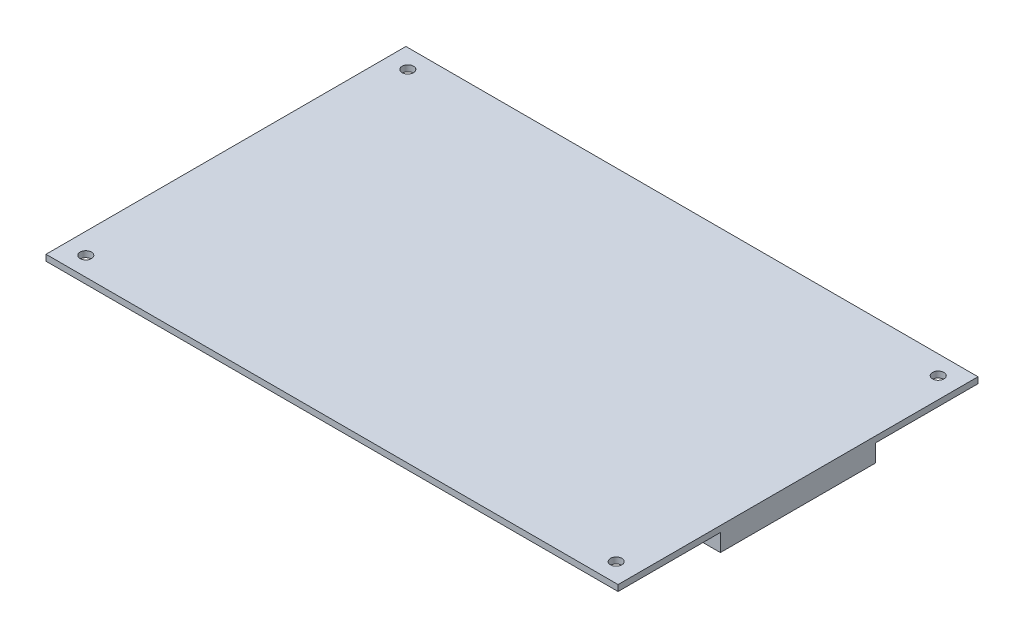
SolidWorks part; units mm, degrees
ref_plane "前视基准面" through (0, 0, 0) normal (0, 0, 1) x (1, 0, 0)
ref_plane "上视基准面" through (0, 0, 0) normal (0, 1, 0) x (1, 0, 0)
ref_plane "右视基准面" through (0, 0, 0) normal (1, 0, 0) x (0, 0, -1)
other "Configuration Table"
sketch "草图1" plane through (0, 0, 0) normal (0, 1, 0) x (1, 0, 0)
  line L1 (0, 0) -> (151, 0)
  line L2 (0, 0) -> (0, -95)
  line L3 (0, -95) -> (151, -95)
  line L4 (151, 0) -> (151, -95)
  dimension "D1" = 151
  dimension "D2" = 95
extrude "凸台-拉伸1" add sketch "草图1" along normal blind 1.6
sketch "草图2" plane through (0, 0, 0) normal (-1, 0, 0) x (0, 0, 1)
  line L0 (0, 0) -> (95, 0) construction
  line L1 (27, 0) -> (68, 0)
  line L2 (27, 0) -> (27, -4.6)
  line L3 (27, -4.6) -> (68, -4.6)
  line L4 (68, 0) -> (68, -4.6)
  line L5 (47.5, 1.6) -> (47.5, -20.1889) construction
  line L6 (0, 1.6) -> (95, 1.6) construction
  dimension "D1" = 4.6
  dimension "D2" = 41
extrude "凸台-拉伸2" add sketch "草图2" along direction (-1, 0, 0) on the side against the normal up to surface (151 mm away)
sketch "草图3" plane through (0, 1.6, 0) normal (0, 1, 0) x (1, 0, 0)
  line L0 (0, -47.5) -> (167.1753, -47.5) construction
  line L1 (0, 0) -> (0, -95) construction
  line L2 (75.5, 0) -> (75.5, -99.7613) construction
  line L3 (151, 0) -> (0, 0) construction
  circle A0 centre (5.5, -5) radius 1.5
  circle A1 centre (5.5, -90) radius 1.5
  circle A2 centre (145.5, -90) radius 1.5
  circle A3 centre (145.5, -5) radius 1.5
  dimension "D1" = 3
  dimension "D2" = 85
  dimension "D3" = 140
extrude "切除-拉伸1" cut sketch "草图3" against normal through all
